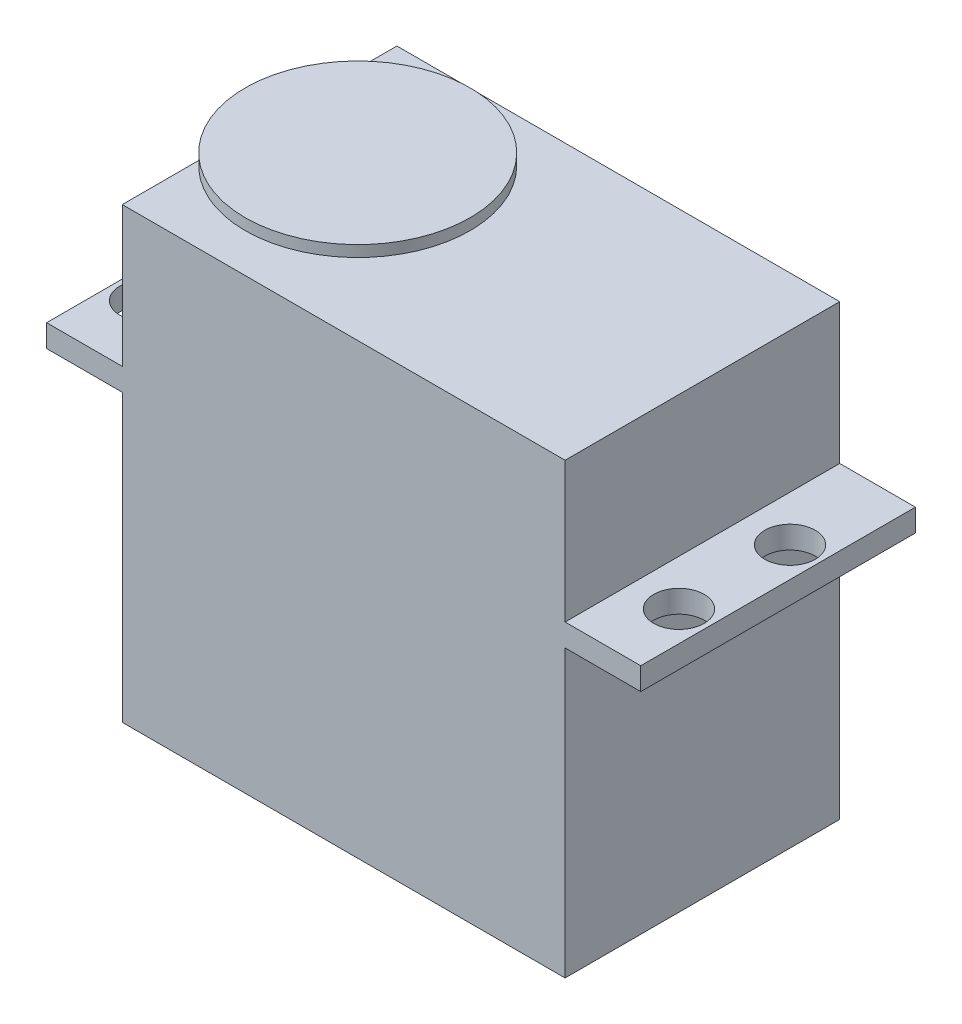
SolidWorks part; units mm, degrees
ref_plane "Front Plane" through (0, 0, 0) normal (0, 0, 1) x (1, 0, 0)
ref_plane "Top Plane" through (0, 0, 0) normal (0, 1, 0) x (1, 0, 0)
ref_plane "Right Plane" through (0, 0, 0) normal (1, 0, 0) x (0, 0, -1)
sketch "Sketch1" plane through (0, 0, 0) normal (0, 1, 0) x (1, 0, 0)
  line L1 (-19.75, 12.25) -> (19.75, 12.25)
  line L2 (-19.75, 12.25) -> (-19.75, -12.25)
  line L3 (-19.75, -12.25) -> (19.75, -12.25)
  line L4 (19.75, 12.25) -> (19.75, -12.25)
  dimension "D1" = 24.5
  dimension "D2" = 39.5
  dimension "D3" = 12.25
  dimension "D4" = 19.75
extrude "Boss-Extrude1" add sketch "Sketch1" along normal blind 40
ref_plane "Plane1" through (0, 27.5, 0) normal (0, 1, 0) x (1, 0, 0)
sketch "Sketch2" plane through (0, 27.5, 0) normal (0, 1, 0) x (1, 0, 0)
  line L1 (-26.5, 12.25) -> (26.5, 12.25)
  line L2 (-26.5, 12.25) -> (-26.5, -12.25)
  line L3 (-26.5, -12.25) -> (26.5, -12.25)
  line L4 (26.5, 12.25) -> (26.5, -12.25)
  dimension "D1" = 24.5
  dimension "D2" = 53
  dimension "D3" = 26.5
  dimension "D4" = 12.25
extrude "Boss-Extrude2" add sketch "Sketch2" against normal blind 2
sketch "Sketch3" plane through (0, 27.5, 0) normal (0, 1, 0) x (1, 0, 0)
  line L0 (-19.75, 12.25) -> (-19.75, -12.25) construction
  line L1 (19.75, -12.25) -> (19.75, 12.25) construction
  line L3 (-26.5, -12.25) -> (-19.75, -12.25) construction
  circle A0 centre (-23.814, 3.752) radius 2.25
  circle A1 centre (-23.814, -6.154) radius 2.25
  circle A2 centre (23.814, 3.752) radius 2.25
  circle A3 centre (23.814, -6.154) radius 2.25
  point P8 (0, 0)
  dimension "D1" = 4.5
  dimension "D2" = 4.064
  dimension "D3" = 4.064
  dimension "D4" = 9.906
  dimension "D5" = 6.096
extrude "Cut-Extrude1" cut sketch "Sketch3" against normal blind 2
sketch "Sketch4" plane through (0, 40, 0) normal (0, 1, 0) x (1, 0, 0)
  line L0 (-19.75, 12.25) -> (-19.75, -12.25) construction
  line L2 (-19.75, -12.25) -> (19.75, -12.25) construction
  circle A0 centre (-9.25, -1.75) radius 2.5
  dimension "D1" = 5
  dimension "D2" = 10.5
  dimension "D3" = 10.5
extrude "Boss-Extrude3" add sketch "Sketch4" along normal blind 3
sketch "Sketch5" plane through (0, 43, 0) normal (0, 1, 0) x (1, 0, 0)
  circle A0 centre (-9.25, -1.75) radius 10.033
  dimension "D1" = 20.066
extrude "Boss-Extrude4" add sketch "Sketch5" along normal blind 1
